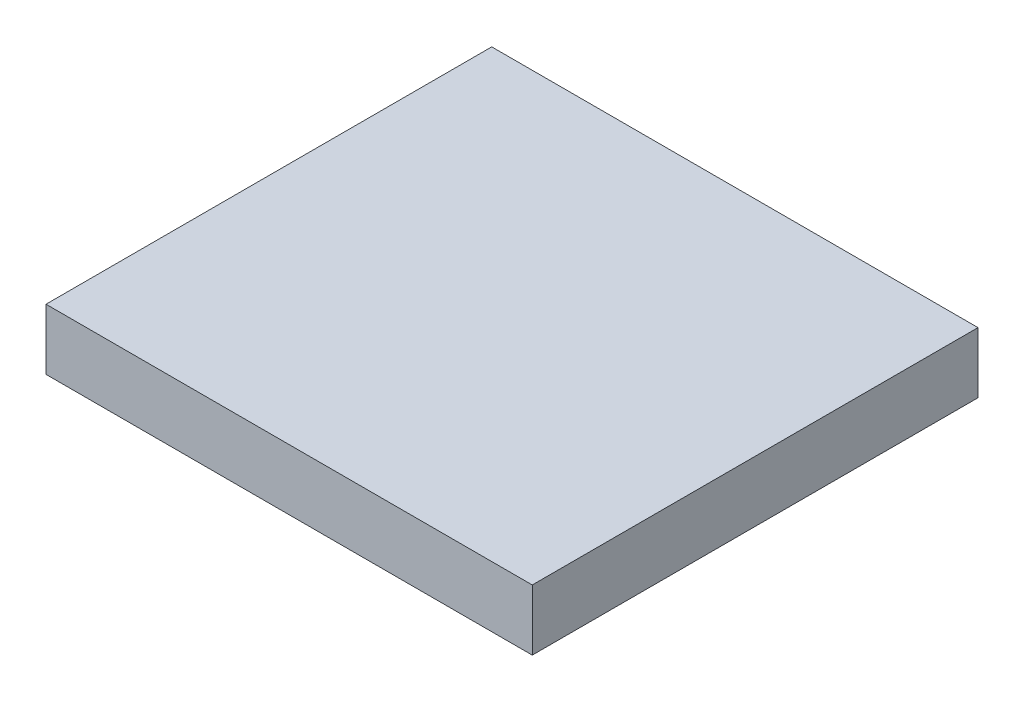
SolidWorks part; units mm, degrees
ref_plane "Front Plane" through (0, 0, 0) normal (0, 0, 1) x (1, 0, 0)
ref_plane "Top Plane" through (0, 0, 0) normal (0, 1, 0) x (1, 0, 0)
ref_plane "Right Plane" through (0, 0, 0) normal (1, 0, 0) x (0, 0, -1)
sketch "Sketch1" plane through (0, 0, 0) normal (0, 0, 1) x (1, 0, 0)
  line L1 (-1200, -230) -> (1200, -230)
  line L2 (-1200, -230) -> (-1200, 70)
  line L3 (-1200, 70) -> (1200, 70)
  line L4 (1200, -230) -> (1200, 70)
extrude "Boss-Extrude1" add sketch "Sketch1" along normal blind 2200 from offset 1100
